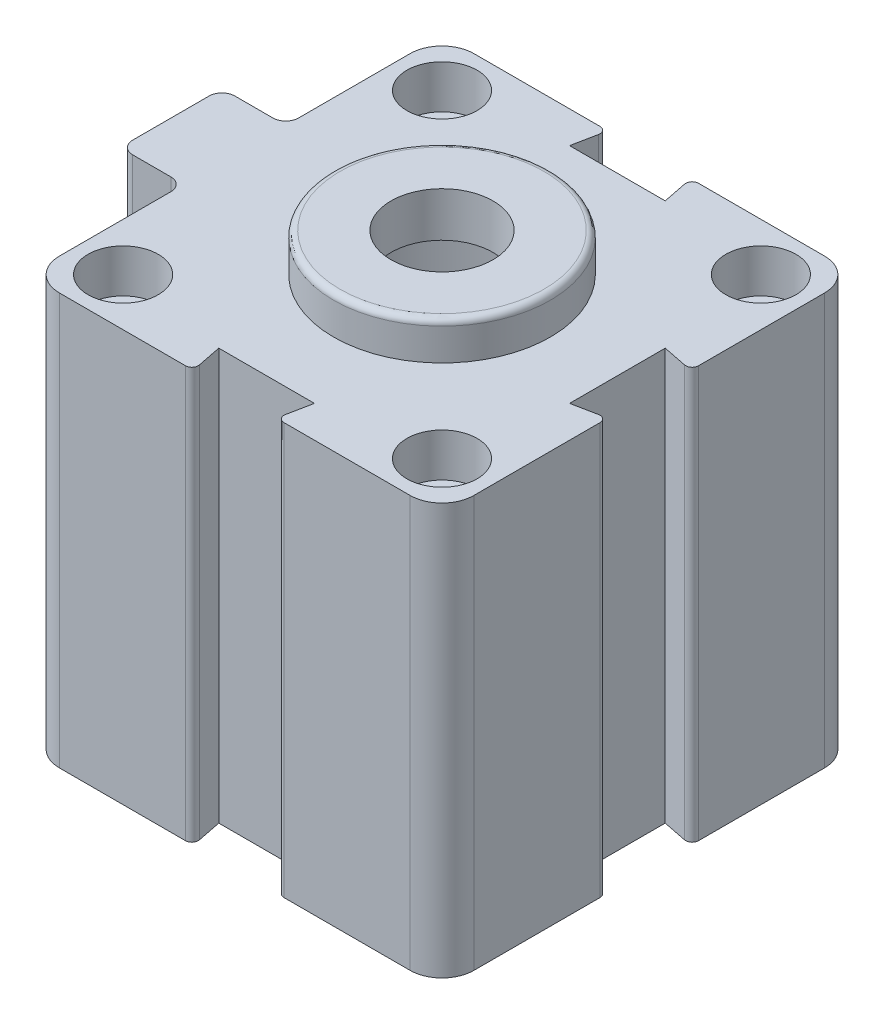
SolidWorks part; units mm, degrees
material "6061 Alloy"
ref_plane "Front Plane" through (0, 0, 0) normal (0, 0, 1) x (1, 0, 0)
ref_plane "Top Plane" through (0, 0, 0) normal (0, 1, 0) x (1, 0, 0)
ref_plane "Right Plane" through (0, 0, 0) normal (1, 0, 0) x (0, 0, -1)
sketch "Sketch1" plane through (0, 0, 0) normal (0, 1, 0) x (1, 0, 0)
  line L0 (0, 72.681) -> (0, -86.4687) construction
  line L1 (-32.5, 32.5) -> (-7.5, 32.5)
  line L2 (-32.5, 32.5) -> (-32.5, 8)
  line L3 (7.5, -32.5) -> (32.5, -32.5)
  line L4 (32.5, 32.5) -> (32.5, 7.5)
  line L5 (-32.5, 32.5) -> (32.5, -32.5) construction
  line L6 (-32.5, -32.5) -> (32.5, 32.5) construction
  line L7 (-90.999, 0) -> (-37.5, 0) construction
  line L8 (-32.5, -8) -> (-32.5, -32.5)
  line L9 (-42.5, -8) -> (-32.5, -8)
  line L10 (-42.5, -8) -> (-42.5, 8)
  line L11 (-42.5, 8) -> (-32.5, 8)
  line L12 (-7.5, 27.5) -> (-6.5, 32.5)
  line L13 (-42.5, -8) -> (-32.5, 8) construction
  line L14 (-42.5, 8) -> (-32.5, -8) construction
  line L15 (-32.5, 0) -> (97.3019, 0) construction
  line L16 (-7.5, 27.5) -> (7.5, 27.5)
  line L17 (-7.5, 32.5) -> (-6.5, 32.5)
  line L18 (6.5, 32.5) -> (7.5, 32.5)
  line L19 (0, -30) -> (7.5, -27.5) construction
  line L20 (-7.5, 27.5) -> (0, 30) construction
  line L21 (-7.5, -27.5) -> (0, -30) construction
  line L22 (7.5, 27.5) -> (6.5, 32.5)
  line L23 (7.5, 32.5) -> (32.5, 32.5)
  line L24 (7.5, -27.5) -> (6.5, -32.5)
  line L25 (0, 30) -> (7.5, 27.5) construction
  line L26 (6.5, -32.5) -> (7.5, -32.5)
  line L27 (-7.5, -32.5) -> (-6.5, -32.5)
  line L28 (-7.5, -27.5) -> (7.5, -27.5)
  line L29 (-7.5, -27.5) -> (-6.5, -32.5)
  line L30 (-7.5, -32.5) -> (-32.5, -32.5)
  line L31 (27.5, 7.5) -> (32.5, 6.5)
  line L32 (32.5, -6.5) -> (32.5, -7.5)
  line L33 (27.5, 7.5) -> (27.5, -7.5)
  line L34 (32.5, 7.5) -> (32.5, 6.5)
  line L36 (27.5, 7.5) -> (32.1875, -6.5625) construction
  line L37 (27.5, -7.5) -> (32.5, 7.5) construction
  line L38 (27.5, -7.5) -> (32.5, -6.5)
  line L40 (32.5, -7.5) -> (32.5, -32.5)
  point P0 (0, 0)
  point P10 (-37.5, 0)
  point P17 (0, 30)
  point P32 (30, 0)
  dimension "D7" = 15
  dimension "D1" = 65
  dimension "D2" = 65
  dimension "D3" = 16
  dimension "D4" = 42.5
  dimension "D5" = 15
  dimension "D6" = 5
  dimension "D8" = 5
  dimension "D9" = 13
  dimension "D10" = 13
extrude "Boss-Extrude1" add sketch "Sketch1" along normal mid plane 64.5
sketch "Sketch2" plane through (0, 32.25, 0) normal (0, 1, 0) x (1, 0, 0)
  line L0 (-56.6907, 0) -> (57.6209, 0) construction
  line L1 (0, 42.9238) -> (0, -45.2009) construction
  circle A0 centre (-25, 25) radius 5.5
  dimension "D1" = 11
  dimension "D2" = 25
  dimension "D3" = 25
extrude "Cut-Extrude1" cut sketch "Sketch2" against normal blind 6.8
pattern_linear "LPattern1" count 2 spacing 50 along (1, 0, 0) count 2 spacing 50 along (0, 0, 1) of "Cut-Extrude1"
mirror "Mirror1" about plane through (0, 0, 0) normal (0, 1, 0) of "LPattern1", "Cut-Extrude1"
sketch "Sketch3" plane through (0, 32.25, 0) normal (0, 1, 0) x (1, 0, 0)
  circle A0 centre (-25, 25) radius 3.3
  dimension "D1" = 6.6
extrude "Cut-Extrude2" cut sketch "Sketch3" against normal blind 63.8
pattern_linear "LPattern2" count 2 spacing 50 along (1, 0, 0) count 2 spacing 50 along (0, 0, 1) of "Cut-Extrude2"
hole_wizard "M10x1.25 Tapped Hole1" positions "Sketch5" profile "Sketch4" tap size "M10x1.25" standard "ANSI Metric"
sketch "Sketch5" plane through (-42.5, 0, 0) normal (-1, 0, 0) x (0, 0, 1)
  line L0 (-8, -32.25) -> (8, -32.25) construction
  point P0 (0, -21.25)
  point P2 (0, 14.25)
  dimension "D1" = 11
  dimension "D2" = 35.5
sketch "Sketch4" plane through (-42.5, -21.25, 0) normal (0, 1, 0) x (0, 0, 1)
  line L0 (0, 0) -> (0, 12.6438)
  line L1 (0, 12.6438) -> (4.4, 10)
  line L2 (4.4, 10) -> (4.4, 0)
  line L5 (4.4, 0) -> (0, 0)
  line L10 (0, 12.6438) -> (-4.4, 10) construction
  line L11 (0, -6.35) -> (0, 107.95) construction
  dimension "Tap Drill Dia." = 8.8
  dimension "Tap Drill Depth" = 10
  dimension "Drill Angle" = 118
sketch "Sketch6" plane through (0, 32.25, 0) normal (0, 1, 0) x (1, 0, 0)
  circle A0 centre (0, 0) radius 25
  dimension "D1" = 50
extrude "Cut-Extrude4" cut sketch "Sketch6" against normal blind 60
sketch "Sketch7" plane through (-42.5, 0, 0) normal (-1, 0, 0) x (0, 0, 1)
  circle A0 centre (-1.0461, 15.7571) radius 0.6
  circle A1 centre (-1.0461, -20.0094) radius 1
  dimension "D1" = 1.2
  dimension "D2" = 2
extrude "Cut-Extrude5" cut sketch "Sketch7" against normal blind 26
fillet "Fillet1" radius 5 4 edges at (32.5, 0, 32.5) (32.5, 0, -32.5) (-32.5, 0, -32.5) (-32.5, 0, 32.5)
fillet "Fillet2" radius 2 4 edges at (-42.5, 0, -8) (-42.5, 0, 8) (-32.5, 0, -8) (-32.5, 0, 8)
fillet "Fillet3" radius 1 6 edges at (32.5, 0, 6.5) (32.5, 0, -6.5) (6.5, 0, 32.5) (-6.5, 0, 32.5) (6.5, 0, -32.5) (-6.5, 0, -32.5)
sketch "Sketch8" plane through (0, 32.25, 0) normal (0, 1, 0) x (1, 0, 0)
  circle A0 centre (0, 0) radius 17
  dimension "D1" = 34
extrude "Boss-Extrude2" add sketch "Sketch8" along normal blind 6
sketch "Sketch9" plane through (0, 32.25, 0) normal (0, 1, 0) x (1, 0, 0)
  circle A0 centre (0, 0) radius 25
extrude "Boss-Extrude3" add sketch "Sketch9" against normal blind 1
fillet "Fillet5" radius 1 1 edges at (0, 38.25, 17)
sketch "Sketch10" plane through (0, 38.25, 0) normal (0, 1, 0) x (1, 0, 0)
  circle A0 centre (0, 0) radius 8
  dimension "D1" = 16
extrude "Cut-Extrude6" cut sketch "Sketch10" against normal blind 38 and the other way blind 87
